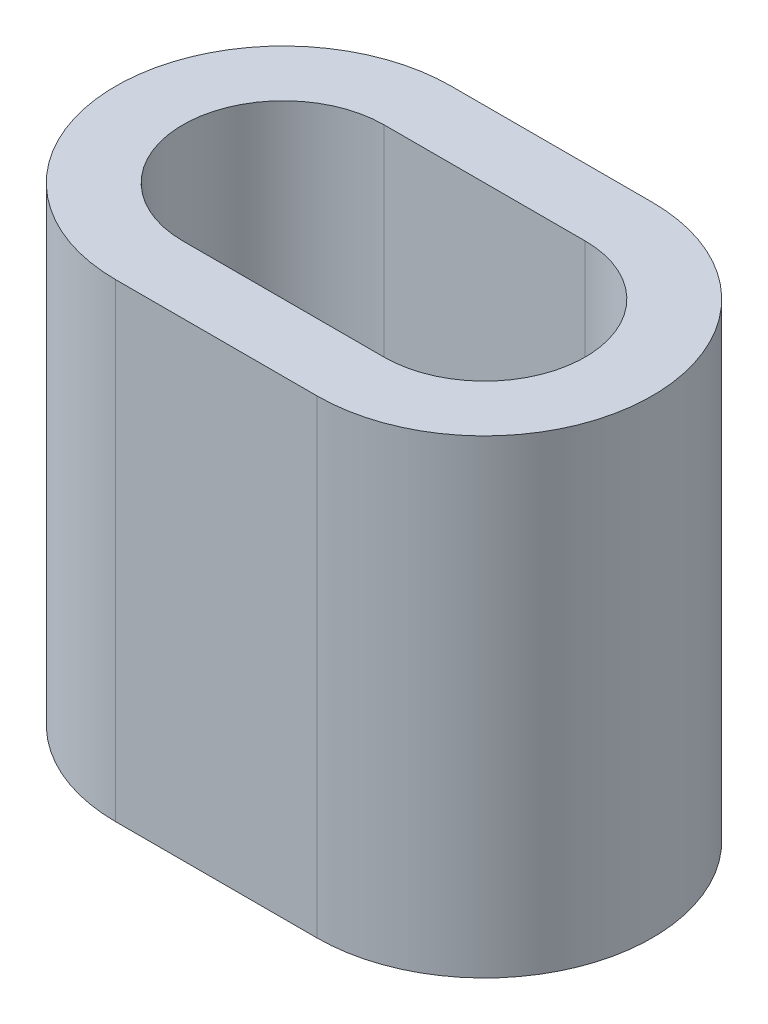
SolidWorks part; units mm, degrees
material "3003 Alloy"
ref_plane "Front Plane" through (0, 0, 0) normal (0, 0, 1) x (1, 0, 0)
ref_plane "Top Plane" through (0, 0, 0) normal (0, 1, 0) x (1, 0, 0)
ref_plane "Right Plane" through (0, 0, 0) normal (1, 0, 0) x (0, 0, -1)
sketch "Sketch1" plane through (0, 0, 0) normal (0, 1, 0) x (1, 0, 0)
  line L0 (1.5, 0) -> (-1.5, 0) construction
  line L1 (1.5, -1.5) -> (-1.5, -1.5)
  line L2 (1.5, 1.5) -> (-1.5, 1.5)
  line L3 (1.5, -2.5) -> (-1.5, -2.5)
  line L4 (1.5, 2.5) -> (-1.5, 2.5)
  arc A0 (1.5, -1.5) -> (1.5, 1.5) centre (1.5, 0) ccw
  arc A1 (-1.5, 1.5) -> (-1.5, -1.5) centre (-1.5, 0) ccw
  arc A2 (-1.5, 2.5) -> (-1.5, -2.5) centre (-1.5, 0) ccw
  arc A3 (1.5, -2.5) -> (1.5, 2.5) centre (1.5, 0) ccw
  point P2 (0, 0)
  dimension "D2" = 6
  dimension "D3" = 3
  dimension "D1" = 1
extrude "Boss-Extrude1" add sketch "Sketch1" along normal mid plane 7
